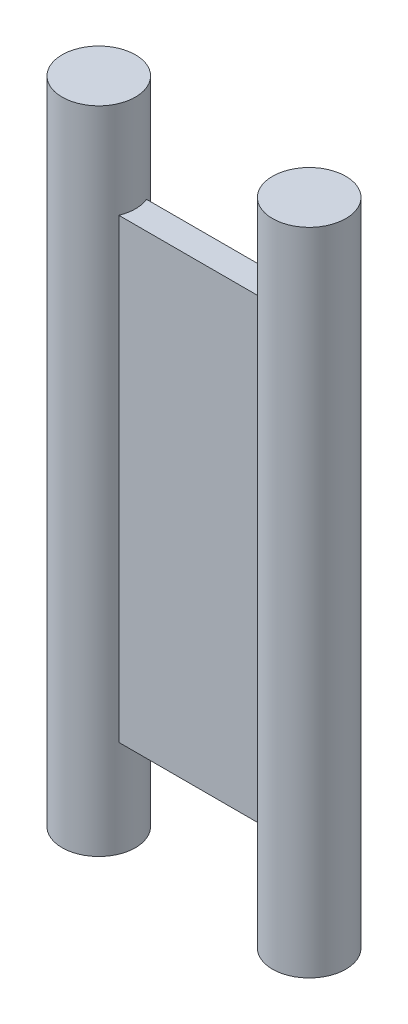
SolidWorks part; units mm, degrees
ref_plane "Front Plane" through (0, 0, 0) normal (0, 0, 1) x (1, 0, 0)
ref_plane "Top Plane" through (0, 0, 0) normal (0, 1, 0) x (1, 0, 0)
ref_plane "Right Plane" through (0, 0, 0) normal (1, 0, 0) x (0, 0, -1)
sketch "Sketch1" plane through (0, 0, 0) normal (0, 1, 0) x (1, 0, 0)
  line L1 (3.803, 0.5) -> (-3.803, 0.5)
  line L2 (3.803, 0.5) -> (3.803, -0.5)
  line L3 (3.803, -0.5) -> (-3.803, -0.5)
  line L4 (-3.803, 0.5) -> (-3.803, -0.5)
  line L5 (3.803, 0.5) -> (-3.803, -0.5) construction
  line L6 (3.803, -0.5) -> (-3.803, 0.5) construction
  point P0 (0, 0)
  dimension "D1" = 7.606
  dimension "D3" = 1
extrude "Boss-Extrude1" add sketch "Sketch1" along normal blind 16.5
ref_plane "Plane1" through (0, 8.25, 0) normal (0, 1, 0) x (1, 0, 0)
sketch "Sketch2" plane through (0, 8.25, 0) normal (0, 1, 0) x (1, 0, 0)
  line L0 (3.803, -0.5) -> (3.803, 0.5) construction
  line L1 (-3.803, 0.5) -> (-3.803, -0.5) construction
  line L2 (3.803, -0.5) -> (3.803, 0.5) construction
  line L3 (-3.803, 0.5) -> (-3.803, -0.5) construction
  circle A0 centre (-3.803, 0) radius 1.325
  circle A1 centre (3.803, 0) radius 1.325
  dimension "D1" = 2.65
extrude "Boss-Extrude2" add sketch "Sketch2" along normal mid plane 23.5
